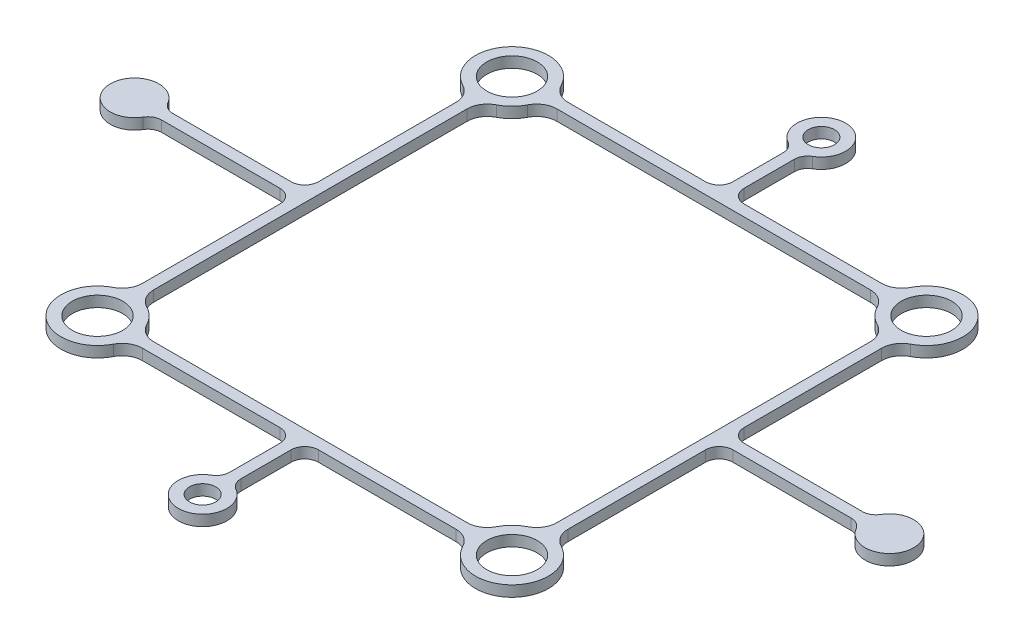
SolidWorks part; units mm, degrees
material "Custom Plastic"
ref_plane "Front Plane" through (0, 0, 0) normal (0, 0, 1) x (1, 0, 0)
ref_plane "Top Plane" through (0, 0, 0) normal (0, 1, 0) x (1, 0, 0)
ref_plane "Right Plane" through (0, 0, 0) normal (1, 0, 0) x (0, 0, -1)
sketch "Sketch1" plane through (0, 0, 0) normal (0, 1, 0) x (1, 0, 0)
  line L0 (0, 0) -> (0, 24.4542) construction
  line L1 (-30.445, -30.445) -> (30.445, -30.445) construction
  line L2 (-30.445, -30.445) -> (-30.445, 30.445) construction
  line L3 (-30.445, 30.445) -> (30.445, 30.445) construction
  line L4 (30.445, -30.445) -> (30.445, 30.445) construction
  line L5 (-30.445, -30.445) -> (30.445, 30.445) construction
  line L6 (-30.445, 30.445) -> (30.445, -30.445) construction
  line L7 (-21.3316, 0) -> (0, 0) construction
  line L8 (-25.1489, 31.27) -> (-0.825, 31.27)
  line L9 (-25.1489, 29.62) -> (25.1489, 29.62)
  line L10 (0, 30.445) -> (0, 45.445) construction
  line L11 (-0.825, 41.9665) -> (-0.825, 31.27)
  line L12 (0.825, 41.9665) -> (0.825, 31.27)
  line L13 (0.825, 31.27) -> (25.1489, 31.27)
  line L14 (0, -30.445) -> (0, -45.445) construction
  line L15 (-25.1489, -29.62) -> (25.1489, -29.62)
  line L16 (30.445, 0) -> (55.445, 0) construction
  line L17 (29.62, -25.1489) -> (29.62, 25.1489)
  line L18 (31.27, 25.1489) -> (31.27, 0.825)
  line L19 (0.825, -31.27) -> (25.1489, -31.27)
  line L20 (-25.1489, -31.27) -> (-0.825, -31.27)
  line L21 (0.825, -41.9665) -> (0.825, -31.27)
  line L22 (-0.825, -41.9665) -> (-0.825, -31.27)
  line L23 (31.27, -0.825) -> (51.9665, -0.825)
  line L24 (-34.155, 30.445) -> (-34.155, 88.2809) construction
  line L25 (34.155, 30.445) -> (34.155, 88.2809) construction
  line L26 (31.27, 0.825) -> (51.9665, 0.825)
  line L27 (31.27, -0.825) -> (31.27, -25.1489)
  line L28 (-30.445, 0) -> (-55.445, 0) construction
  line L29 (-31.27, -0.825) -> (-51.9665, -0.825)
  line L30 (-31.27, -0.825) -> (-31.27, -25.1489)
  line L31 (-31.27, 0.825) -> (-51.9665, 0.825)
  line L32 (-31.27, 25.1489) -> (-31.27, 0.825)
  line L33 (-29.62, -25.1489) -> (-29.62, 25.1489)
  arc A0 (-29.62, 25.1489) -> (-25.1489, 29.62) centre (-30.445, 30.445) ccw
  circle A1 centre (-30.445, 30.445) radius 3.71
  circle A2 centre (30.445, 30.445) radius 3.71
  arc A3 (25.1489, 31.27) -> (31.27, 25.1489) centre (30.445, 30.445) cw
  arc A4 (29.62, -25.1489) -> (25.1489, -29.62) centre (30.445, -30.445) ccw
  circle A5 centre (30.445, -30.445) radius 3.71
  arc A6 (-25.1489, -31.27) -> (-31.27, -25.1489) centre (-30.445, -30.445) cw
  circle A7 centre (-30.445, -30.445) radius 3.71
  circle A8 centre (0, 45.445) radius 1.925
  arc A9 (0.825, 41.9665) -> (-0.825, 41.9665) centre (0, 45.445) ccw
  arc A11 (51.9665, -0.825) -> (51.9665, 0.825) centre (55.445, 0) ccw
  circle A12 centre (0, -45.445) radius 1.925
  arc A13 (0.825, -41.9665) -> (-0.825, -41.9665) centre (0, -45.445) cw
  arc A15 (-51.9665, -0.825) -> (-51.9665, 0.825) centre (-55.445, 0) cw
  arc A16 (-25.1489, 31.27) -> (-31.27, 25.1489) centre (-30.445, 30.445) ccw
  arc A18 (29.62, 25.1489) -> (25.1489, 29.62) centre (30.445, 30.445) cw
  arc A20 (25.1489, -31.27) -> (31.27, -25.1489) centre (30.445, -30.445) ccw
  arc A22 (-29.62, -25.1489) -> (-25.1489, -29.62) centre (-30.445, -30.445) cw
  point P0 (0, 0)
  dimension "D1" = 1.65
  dimension "D2" = 15
  dimension "D5" = 7.42
  dimension "D6" = 3.85
  dimension "D8" = 1.65
  dimension "D12" = 0.825
  dimension "D3" = 0.825
  dimension "D4" = 0.825
  dimension "D7" = 68.31
  dimension "D9" = 0.825
  dimension "D10" = 0.825
  dimension "D11" = 0.825
  dimension "D15" = 0.825
  dimension "D16" = 0.825
  dimension "D17" = 25
extrude "Boss-Extrude1" add sketch "Sketch1" along normal blind 1.5875
fillet "Fillet1" radius 3 16 edges at (-25.1489, 0.7937, 31.27) (-25.1489, 0.7937, 29.62) (-29.62, 0.7937, 25.1489) (-31.27, 0.7937, 25.1489) (31.27, 0.7937, 25.1489) (29.62, 0.7937, 25.1489) (25.1489, 0.7937, 29.62) (25.1489, 0.7937, 31.27) (25.1489, 0.7937, -31.27) (25.1489, 0.7937, -29.62) (29.62, 0.7937, -25.1489) (31.27, 0.7937, -25.1489) (-25.1489, 0.7937, -31.27) (-31.27, 0.7937, -25.1489) (-29.62, 0.7937, -25.1489) (-25.1489, 0.7937, -29.62)
fillet "Fillet2" radius 2 8 edges at (0.825, 0.7937, -31.27) (-0.825, 0.7937, -31.27) (-31.27, 0.7937, 0.825) (-31.27, 0.7937, -0.825) (-0.825, 0.7937, 31.27) (0.825, 0.7937, 31.27) (31.27, 0.7937, 0.825) (31.27, 0.7937, -0.825)
fillet "Fillet3" radius 2 8 edges at (-0.825, 0.7937, -41.9665) (0.825, 0.7937, -41.9665) (-51.9665, 0.7937, 0.825) (-51.9665, 0.7937, -0.825) (51.9665, 0.7937, 0.825) (51.9665, 0.7937, -0.825) (-0.825, 0.7937, 41.9665) (0.825, 0.7937, 41.9665)
